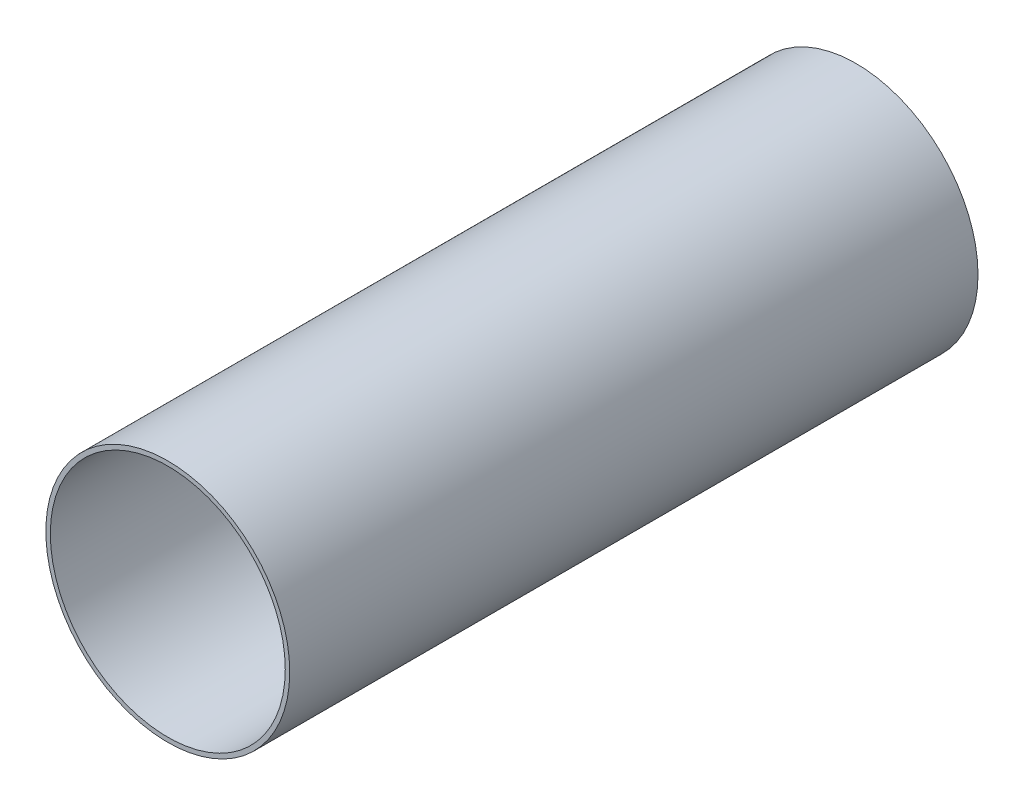
SolidWorks part; units mm, degrees
ref_plane "Front Plane" through (0, 0, 0) normal (0, 0, 1) x (1, 0, 0)
ref_plane "Top Plane" through (0, 0, 0) normal (0, 1, 0) x (1, 0, 0)
ref_plane "Right Plane" through (0, 0, 0) normal (1, 0, 0) x (0, 0, -1)
sketch "Sketch1" plane through (0, 0, 0) normal (0, 0, 1) x (1, 0, 0)
  circle A0 centre (0, 0) radius 47.6885
  circle A1 centre (0, 0) radius 49.5046
  dimension "D1" = 95.377
  dimension "D2" = 99.0092
extrude "Boss-Extrude1" add sketch "Sketch1" along normal blind 279.4
